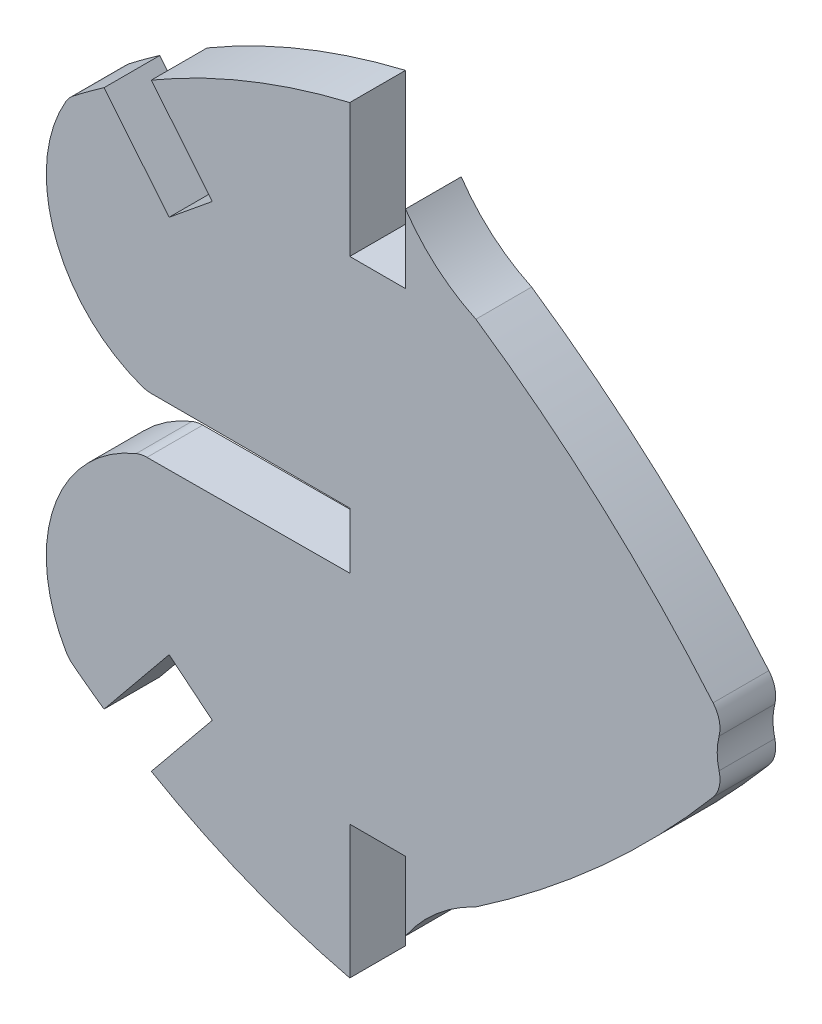
SolidWorks part; units mm, degrees
ref_plane "Front Plane" through (0, 0, 0) normal (0, 0, 1) x (1, 0, 0)
ref_plane "Top Plane" through (0, 0, 0) normal (0, 1, 0) x (1, 0, 0)
ref_plane "Right Plane" through (0, 0, 0) normal (1, 0, 0) x (0, 0, -1)
sketch "Sketch1" plane through (0, 0, 0) normal (0, 0, 1) x (1, 0, 0)
  line L1 (70.3518, -1.5404) -> (70.3518, 0)
  line L3 (71.1116, -11.293) -> (71.1116, -7.483) construction
  line L4 (71.1116, 9.769) -> (71.1116, 5.959) construction
  line L5 (70.3496, 9.6026) -> (70.3496, 5.959)
  line L6 (71.8736, -9.3684) -> (71.8736, -7.483)
  line L8 (70.3518, 0) -> (64.9298, 0)
  line L9 (71.8736, 7.8444) -> (71.8736, 5.959)
  line L10 (70.3496, -11.1266) -> (70.3496, -7.483)
  line L11 (63.9401, 7.4224) -> (66.0008, 4.8985) construction
  line L12 (70.3518, -1.5404) -> (64.8049, -1.5704)
  line L13 (70.3496, 5.959) -> (71.8736, 5.959)
  line L14 (70.3496, 9.769) -> (70.3496, 5.959) construction
  line L15 (71.8736, -7.483) -> (70.3496, -7.483)
  line L16 (71.8736, -11.293) -> (71.8736, -7.483) construction
  line L17 (70.3496, -11.293) -> (70.3496, -7.483) construction
  line L18 (71.8736, 9.769) -> (71.8736, 5.959) construction
  line L19 (63.6315, 6.5955) -> (65.4106, 4.4165)
  line L20 (64.9245, 7.4216) -> (66.5911, 5.3804)
  line L21 (65.4106, -5.9405) -> (66.5911, -6.9044)
  line L22 (65.4106, 4.4165) -> (66.5911, 5.3804)
  line L23 (63.3498, 6.9405) -> (65.4106, 4.4165) construction
  line L24 (64.5303, 7.9044) -> (66.5911, 5.3804) construction
  line L25 (64.9245, -8.9456) -> (66.5911, -6.9044)
  line L26 (63.6315, -8.1195) -> (65.4106, -5.9405)
  arc A0 (73.7975, 6.1965) -> (80.2836, 0.3557) centre (55.6042, -20.5286) cw
  arc A1 (70.3496, 9.6026) -> (64.9245, 7.4216) centre (74.9682, -9.7236) ccw
  arc A2 (73.7975, -7.7205) -> (71.8736, -9.3684) centre (75.8398, -12.0518) ccw
  arc A3 (62.5889, 5.7485) -> (64.6603, 0.0471) centre (66.0008, 3.7611) ccw
  arc A4 (73.7975, 6.1965) -> (71.8736, 7.8444) centre (75.8398, 10.5278) cw
  arc A5 (62.5889, 5.7485) -> (62.7883, 5.9761) centre (63.2748, 5.349) cw
  arc A6 (64.6603, 0.0471) -> (64.9298, 0) centre (64.9298, 0.7937) ccw
  arc A7 (62.5889, -7.2725) -> (62.7883, -7.5001) centre (63.2748, -6.873) ccw
  arc A8 (63.6315, 6.5955) -> (62.7883, 5.9761) centre (74.9682, -9.7236) ccw
  arc A9 (62.5889, -7.2725) -> (64.5093, -1.6292) centre (66.0008, -5.2851) cw
  arc A10 (63.6315, -8.1195) -> (62.7883, -7.5001) centre (74.9682, 8.1996) cw
  arc A11 (70.3496, -11.1266) -> (64.9245, -8.9456) centre (74.9682, 8.1996) cw
  arc A12 (73.7975, -7.7205) -> (80.2836, -1.8797) centre (55.6042, 19.0046) ccw
  arc A13 (64.5093, -1.6292) -> (64.8049, -1.5704) centre (64.8091, -2.3641) cw
  arc A14 (80.447, -1.1718) -> (80.447, -0.3522) centre (82.0624, -0.762) cw
  arc A15 (80.2836, -1.8797) -> (80.447, -1.1718) centre (79.6776, -1.367) ccw
  arc A16 (80.2836, 0.3557) -> (80.447, -0.3522) centre (79.6776, -0.157) cw
  point P48 (64.6603, -1.5711)
  point P49 (80.5803, -1.524)
  point P52 (80.5803, 0)
  dimension "D2" = 0.762
  dimension "D3" = 0.7937
  dimension "D4" = 0.7937
  dimension "D5" = 0.7937
  dimension "D6" = 0.762
  dimension "D7" = 0.762
  dimension "D8" = 0.762
extrude "Boss-Extrude1" add sketch "Sketch1" along normal blind 1.524
